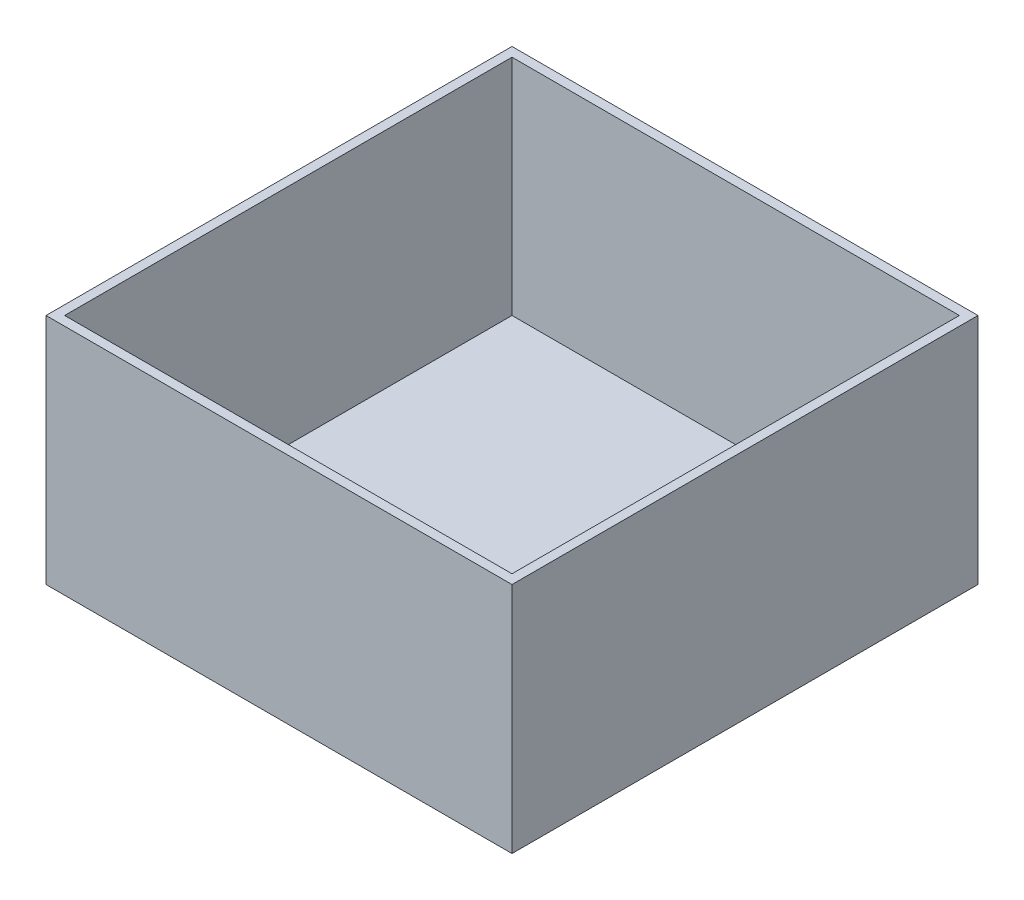
SolidWorks part; units mm, degrees
ref_plane "Plan de face" through (0, 0, 0) normal (0, 0, 1) x (1, 0, 0)
ref_plane "Plan de dessus" through (0, 0, 0) normal (0, 1, 0) x (1, 0, 0)
ref_plane "Plan de droite" through (0, 0, 0) normal (1, 0, 0) x (0, 0, -1)
sketch "Esquisse1" plane through (0, 0, 0) normal (0, 1, 0) x (1, 0, 0)
  line L1 (-145.9194, 401.3386) -> (354.0806, 401.3386)
  line L2 (-145.9194, 401.3386) -> (-145.9194, -98.6614)
  line L3 (-145.9194, -98.6614) -> (354.0806, -98.6614)
  line L4 (354.0806, 401.3386) -> (354.0806, -98.6614)
extrude "Boss.-Extru.1" add sketch "Esquisse1" along normal blind 250
shell "Coque1" thickness 10
